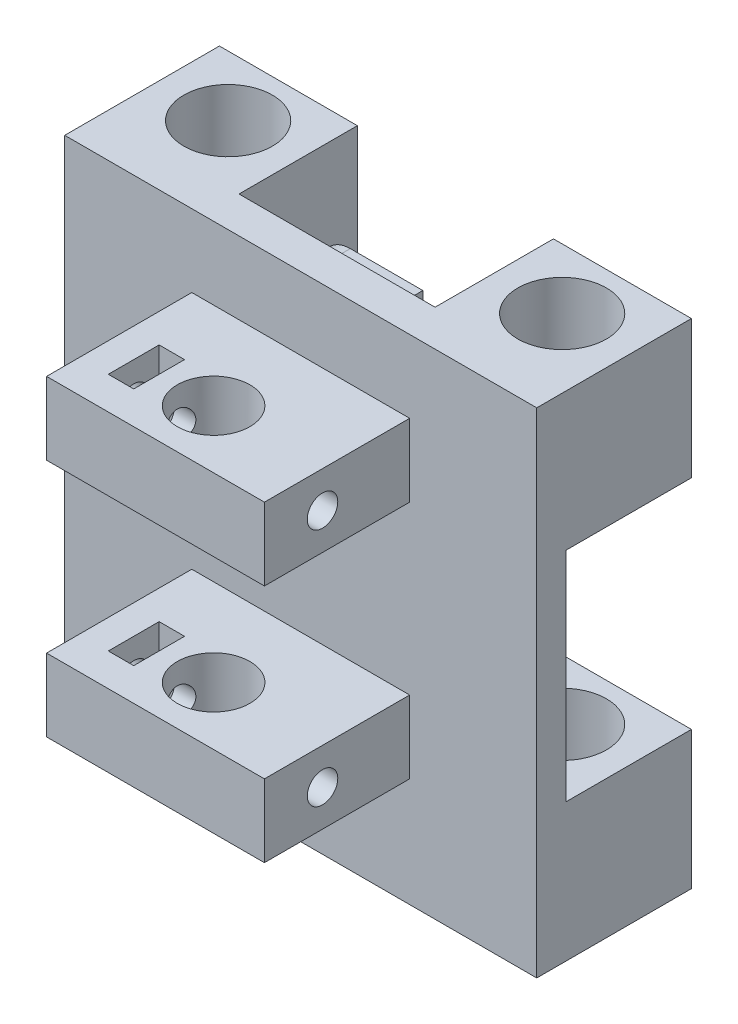
SolidWorks part; units mm, degrees
ref_plane "Front Plane" through (0, 0, 0) normal (0, 0, 1) x (1, 0, 0)
ref_plane "Top Plane" through (0, 0, 0) normal (0, 1, 0) x (1, 0, 0)
ref_plane "Right Plane" through (0, 0, 0) normal (1, 0, 0) x (0, 0, -1)
sketch "Sketch1" plane through (0, 0, 0) normal (0, 1, 0) x (1, 0, 0)
  line L0 (-23, 0) -> (23, 0) construction
  line L1 (-32.5, 9) -> (-13.5, 9)
  line L2 (-13.5, 9) -> (-13.5, -8)
  line L3 (-13.5, -8) -> (-32.5, -8)
  line L4 (-32.5, -8) -> (-32.5, 9)
  line L5 (0, 16.9538) -> (0, -28.3436) construction
  line L6 (13.5, 9) -> (13.5, -8)
  line L7 (32.5, 9) -> (13.5, 9)
  line L8 (32.5, -8) -> (32.5, 9)
  line L9 (13.5, -8) -> (32.5, -8)
  line L10 (-32.5, -8) -> (-32.5, -13)
  line L11 (-32.5, -13) -> (32.5, -13)
  line L12 (32.5, -13) -> (32.5, -8)
  line L13 (-13.5, -8) -> (13.5, -8)
  circle A0 centre (-23, 0) radius 6.1
  circle A1 centre (23, 0) radius 6.1
  point P3 (0, 0)
  dimension "D2" = 12.2
  dimension "D3" = 12.2
  dimension "D1" = 46
  dimension "D4" = 17
  dimension "D5" = 19
  dimension "D6" = 9.5
  dimension "D7" = 8
  dimension "D8" = 5
extrude "Boss-Extrude1" add sketch "Sketch1" along normal blind 68 contours L4 L3 L2 L1 A0 | L6 L9 L8 L7 A1 | L13 L3 L10 L11 L12 L9
ref_plane "Plane1" through (0, 0, -9) normal (0, 0, -1) x (-1, 0, 0)
sketch "Sketch3" plane through (0, 0, -9) normal (0, 0, -1) x (-1, 0, 0)
  line L0 (-32.5, 0) -> (-32.5, 19) construction
  line L1 (-32.5, 68) -> (-32.5, 0) construction
  line L2 (-32.5, 68) -> (-32.5, 49) construction
  line L3 (-32.5, 49) -> (32.5, 49)
  line L4 (32.5, 68) -> (32.5, 0) construction
  line L5 (-32.5, 19) -> (32.5, 19)
  line L6 (32.5, 19) -> (32.5, 49)
  line L7 (-32.5, 19) -> (-32.5, 49)
  dimension "D1" = 19
extrude "Cut-Extrude1" cut sketch "Sketch3" against normal up to surface (17 mm away) up to face at (0, 34, 8)
sketch "Sketch4" plane through (0, 0, 8) normal (0, 0, -1) x (-1, 0, 0)
  line L0 (11.2, 68) -> (11.2, 60.15) construction
  line L1 (13.5, 68) -> (-13.5, 68) construction
  line L2 (11.2, 60.15) -> (13.5, 60.15) construction
  line L3 (13.5, 68) -> (13.5, 49) construction
  line L4 (11.2, 60.15) -> (5.3, 60.15)
  line L5 (2.7063, 62.5) -> (2.7063, 57.8)
  line L7 (-6.7, 62.15) -> (2.7063, 62.5)
  line L9 (-6.7, 58.15) -> (2.7063, 57.8)
  line L11 (-8.821, 58.15) -> (-3.821, 58.15)
  line L12 (-3.821, 58.15) -> (-3.821, 54.15)
  line L13 (-3.821, 54.15) -> (-8.821, 54.15)
  line L14 (-8.821, 54.15) -> (-8.821, 58.15)
  line L16 (-8.821, 62.15) -> (1.179, 62.15)
  line L17 (1.179, 62.15) -> (1.179, 66.15)
  line L18 (1.179, 66.15) -> (-8.821, 66.15)
  line L19 (-8.821, 66.15) -> (-8.821, 62.15)
  circle A0 centre (5.3, 60.15) radius 5.9 construction
  circle A2 centre (5.3, 60.15) radius 3.5
  circle A4 centre (-6.7, 60.15) radius 2
  circle A5 centre (5.3, 60.15) radius 12 construction
  arc A6 (-2.821, 62.15) -> (1.179, 66.15) centre (1.179, 62.15) ccw
  arc A7 (1.179, 62.15) -> (4.1912, 59.5181) centre (1.3692, 59.328) cw
  dimension "D2" = 7
  dimension "D3" = 11.8
  dimension "D5" = 4.7
  dimension "D6" = 4
  dimension "D1" = 2.3
  dimension "D4" = 7.85
  dimension "D7" = 12
  dimension "D8" = 9.4063
extrude "Boss-Extrude2" add sketch "Sketch4" along normal blind 3 contours L18 L19 L16 L7 L17 | L16 L17 L7 | L14 L13 L12 L9 L11 | L12 L11 L9 | L5 A7 A6 A2 | A2 A6 L17 L7 | L17 A7 A2 L7 | A2 A7 L5
sketch "Sketch5" plane through (0, 0, 13) normal (0, 0, 1) x (1, 0, 0)
  line L0 (-15, 15) -> (15, 15)
  line L1 (-32.5, 0) -> (32.5, 0) construction
  line L2 (-3.5, -21.2953) -> (3.5, -21.2953) construction
  line L3 (0, -24.8) -> (-3.5, -21.2953) construction
  line L4 (0, -24.8) -> (3.5, -21.2953) construction
  line L5 (-3.5, -21.2953) -> (-3.5, 113.7047) construction
  line L6 (3.5, -21.2953) -> (3.5, 113.7047) construction
  line L7 (3.5, 113.7047) -> (-3.5, 113.7047) construction
  line L8 (-15, 15) -> (-15, 25)
  line L9 (-15, 25) -> (15, 25)
  line L10 (15, 25) -> (15, 15)
  line L11 (-15, 48) -> (15, 48)
  line L12 (15, 48) -> (15, 58)
  line L13 (15, 58) -> (-15, 58)
  line L14 (-15, 58) -> (-15, 48)
  line L15 (-32.5, 68) -> (32.5, 68) construction
  line L16 (0, -24.8) -> (0, 15) construction
  line L17 (0, 58) -> (0, 15) construction
  point P2 (0, 15)
  dimension "D1" = 15
  dimension "D2" = 10
  dimension "D3" = 10
  dimension "D4" = 10
extrude "Boss-Extrude3" add sketch "Sketch5" along normal blind 20
sketch "Sketch6" plane through (0, 58, 0) normal (0, 1, 0) x (1, 0, 0)
  circle A0 centre (0, -25) radius 5
  dimension "D1" = 10
extrude "Cut-Extrude2" cut sketch "Sketch6" against normal through all
ref_plane "Plane2" through (-15, 0, 0) normal (-1, 0, 0) x (0, 0, 1)
sketch "Sketch8" plane through (-15, 0, 0) normal (-1, 0, 0) x (0, 0, 1)
  circle A0 centre (25, 20) radius 2.1
  circle A1 centre (25, 53) radius 2.1
  dimension "D1" = 4.2
  dimension "D2" = 4.2
extrude "Cut-Extrude3" cut sketch "Sketch8" against normal through all
sketch "Sketch9" plane through (0, 15, 0) normal (0, -1, 0) x (1, 0, 0)
  line L0 (0, 25) -> (-15, 25) construction
  line L1 (-15, 12.4158) -> (-15, -12.4158) construction
  line L2 (-15, 25) -> (-11, 25)
  line L3 (-11, 21.5) -> (-11, 28.5)
  line L4 (-11, 21.5) -> (-7.5, 21.5)
  line L5 (-7.5, 21.5) -> (-7.5, 28.5)
  line L6 (-7.5, 28.5) -> (-11, 28.5)
  dimension "D1" = 4
  dimension "D2" = 7
  dimension "D3" = 3.5
extrude "Cut-Extrude4" cut sketch "Sketch9" against normal up to surface (43 mm away) contours L5 L0 L3 L4 | L0 L5 L6 L3 up to face at (0, 58, 30)
sketch "Sketch10" plane through (0, 0, -9) normal (0, 0, -1) x (-1, 0, 0)
  line L0 (32.5, 19) -> (13.5, 19) construction
  line L1 (13.5, 19) -> (13.5, 0) construction
  line L2 (13.5, 0) -> (32.5, 0) construction
  line L3 (32.5, 0) -> (32.5, 19) construction
  line L4 (-13.5, 0) -> (-13.5, 19) construction
  line L5 (-13.5, 19) -> (-32.5, 19) construction
  line L6 (-32.5, 19) -> (-32.5, 0) construction
  line L7 (-32.5, 0) -> (-13.5, 0) construction
  line L8 (13.5, 49) -> (32.5, 49) construction
  line L9 (32.5, 49) -> (32.5, 68) construction
  line L10 (32.5, 68) -> (13.5, 68) construction
  line L11 (13.5, 68) -> (13.5, 49) construction
  line L12 (-32.5, 68) -> (-32.5, 49) construction
  line L13 (-32.5, 49) -> (-13.5, 49) construction
  line L14 (-13.5, 49) -> (-13.5, 68) construction
  line L15 (-13.5, 68) -> (-32.5, 68) construction
  line L16 (32.5, 19) -> (13.5, 19)
  line L17 (13.5, 19) -> (13.5, 0)
  line L18 (13.5, 0) -> (32.5, 0)
  line L19 (32.5, 0) -> (32.5, 19)
  line L20 (-13.5, 0) -> (-13.5, 19)
  line L21 (-13.5, 19) -> (-32.5, 19)
  line L22 (-32.5, 19) -> (-32.5, 0)
  line L23 (-32.5, 0) -> (-13.5, 0)
  line L24 (13.5, 49) -> (32.5, 49)
  line L25 (32.5, 49) -> (32.5, 68)
  line L26 (32.5, 68) -> (13.5, 68)
  line L27 (13.5, 68) -> (13.5, 49)
  line L28 (-32.5, 68) -> (-32.5, 49)
  line L29 (-32.5, 49) -> (-13.5, 49)
  line L30 (-13.5, 49) -> (-13.5, 68)
  line L31 (-13.5, 68) -> (-32.5, 68)
extrude "Cut-Extrude5" cut sketch "Sketch10" against normal blind 0.7
sketch "Sketch11" plane through (0, 0, 8) normal (0, 0, -1) x (-1, 0, 0)
  line L0 (32.5, 19) -> (-32.5, 19)
  line L1 (-32.5, 19) -> (-32.5, 49)
  line L2 (-32.5, 49) -> (32.5, 49)
  line L3 (32.5, 49) -> (32.5, 19)
extrude "Cut-Extrude6" cut sketch "Sketch11" against normal blind 1
